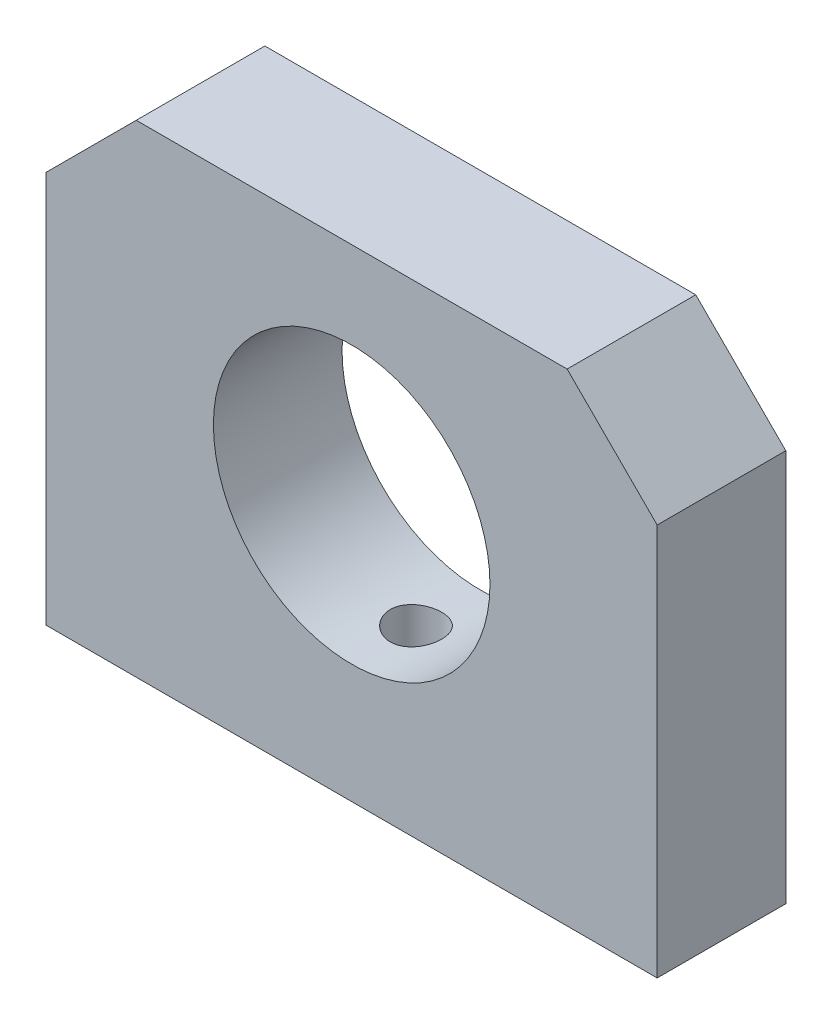
SolidWorks part; units mm, degrees
ref_plane "Piano frontale" through (0, 0, 0) normal (0, 0, 1) x (1, 0, 0)
ref_plane "Piano superiore" through (0, 0, 0) normal (0, 1, 0) x (1, 0, 0)
ref_plane "Piano destro" through (0, 0, 0) normal (1, 0, 0) x (0, 0, -1)
sketch "Schizzo1" plane through (0, 0, 0) normal (0, 0, 1) x (1, 0, 0)
  line L0 (47.5, 75) -> (47.5, 0) construction
  line L1 (0, 0) -> (95, 0)
  line L2 (0, 0) -> (0, 61)
  line L3 (14, 75) -> (81, 75)
  line L4 (95, 0) -> (95, 61)
  line L5 (0, 37.5) -> (95, 37.5) construction
  line L6 (0, 61) -> (14, 75)
  line L7 (81, 75) -> (95, 61)
  circle A0 centre (47.5, 40) radius 21.5
  point P1 (95, 75)
  point P2 (0, 75)
  dimension "D4" = 43
  dimension "D1" = 75
  dimension "D2" = 95
  dimension "D3" = 40
extrude "Estrusione-Estrusione1" add sketch "Schizzo1" along normal blind 20
sketch "Schizzo2" plane through (0, 0, 0) normal (0, -1, 0) x (1, 0, 0)
  line L0 (0, 10) -> (95, 10) construction
  line L1 (0, 20) -> (0, 0) construction
  line L2 (95, 20) -> (95, 0) construction
  line L3 (47.5, 20) -> (47.5, 0) construction
  line L4 (0, 20) -> (95, 20) construction
  line L5 (0, 0) -> (95, 0) construction
  circle A0 centre (47.5, 10) radius 4
  circle A1 centre (17.5, 10) radius 4
  circle A2 centre (77.5, 10) radius 4
  dimension "D1" = 8
  dimension "D2" = 30
extrude "Taglio-Estrusione1" cut sketch "Schizzo2" against normal blind 20
